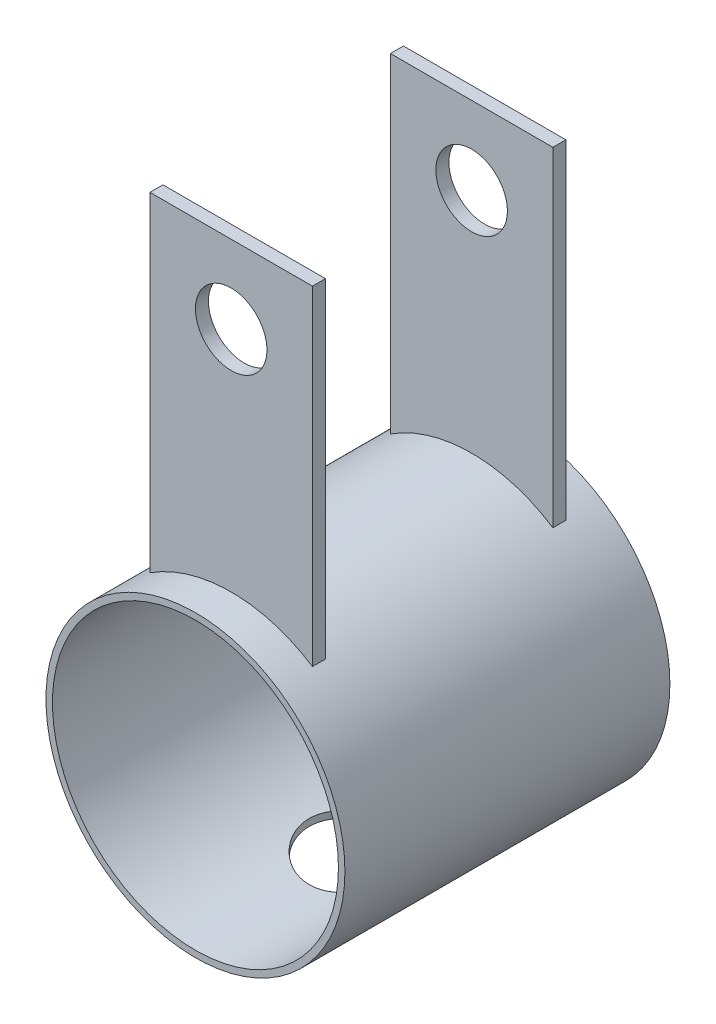
SolidWorks part; units mm, degrees
ref_plane "Plano frontal" through (0, 0, 0) normal (0, 0, 1) x (1, 0, 0)
ref_plane "Plano superior" through (0, 0, 0) normal (0, 1, 0) x (1, 0, 0)
ref_plane "Plano direito" through (0, 0, 0) normal (1, 0, 0) x (0, 0, -1)
sketch "Esboço1" plane through (0, 0, 0) normal (0, 0, 1) x (1, 0, 0)
  circle A0 centre (0, 0) radius 22
  circle A1 centre (0, 0) radius 23
  dimension "D1" = 44
  dimension "D2" = 46
extrude "Ressalto-extrusão1" add sketch "Esboço1" along normal blind 50
sketch "Esboço2" plane through (0, 0, 0) normal (0, 1, 0) x (1, 0, 0)
  circle A0 centre (0, -25) radius 7.5
  dimension "D1" = 15
extrude "Corte-extrusão1" cut sketch "Esboço2" against normal blind 50
sketch "Esboço3" plane through (0, 0, 0) normal (0, 1, 0) x (1, 0, 0)
  line L0 (23, -25) -> (0, -25)
  line L1 (23, -50) -> (23, 0) construction
  line L3 (0, -7.5) -> (-12.5, -7.5)
  line L4 (-12.5, -7.5) -> (-12.5, -5.5)
  line L5 (-12.5, -5.5) -> (12.5, -5.5)
  line L6 (12.5, -5.5) -> (12.5, -7.5)
  line L7 (12.5, -7.5) -> (0, -7.5)
  line L9 (0, -42.5) -> (-12.5, -42.5)
  line L10 (-12.5, -42.5) -> (-12.5, -44.5)
  line L11 (-12.5, -44.5) -> (12.5, -44.5)
  line L12 (12.5, -44.5) -> (12.5, -42.5)
  line L13 (12.5, -42.5) -> (0, -42.5)
  dimension "D1" = 17.5
  dimension "D2" = 12.5
  dimension "D3" = 2
  dimension "D4" = 25
  dimension "D5" = 2
  dimension "D6" = 17.5
  dimension "D7" = 12.5
  dimension "D8" = 2
  dimension "D9" = 25
extrude "Ressalto-extrusão2" add sketch "Esboço3" along normal blind 70 contours L9 L10 L11 L12 L13 | L5 L6 L7 L3 L4
sketch "Esboço4" plane through (0, 0, 5.5) normal (0, 0, -1) x (-1, 0, 0)
  circle A0 centre (0, 0) radius 22
extrude "Corte-extrusão2" cut sketch "Esboço4" against normal blind 70
sketch "Esboço7" plane through (0, 0, 5.5) normal (0, 0, -1) x (-1, 0, 0)
  line L0 (0, 23) -> (0, 58)
  arc A0 (12.5, 19.3067) -> (-12.5, 19.3067) centre (0, 0) ccw construction
  circle A1 centre (0, 58) radius 5.5
  dimension "D2" = 11
  dimension "D1" = 35
extrude "Corte-extrusão4" cut sketch "Esboço7" against normal blind 70
